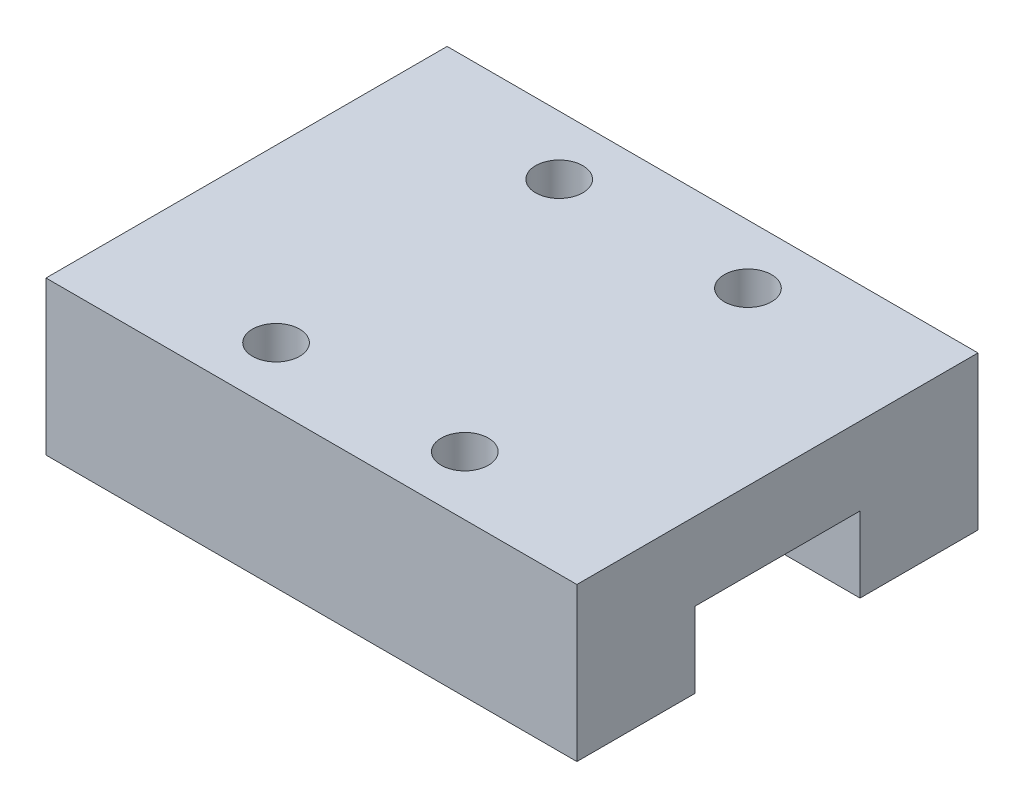
SolidWorks part; units mm, degrees
ref_plane "前视基准面" through (0, 0, 0) normal (0, 0, 1) x (1, 0, 0)
ref_plane "上视基准面" through (0, 0, 0) normal (0, 1, 0) x (1, 0, 0)
ref_plane "右视基准面" through (0, 0, 0) normal (1, 0, 0) x (0, 0, -1)
other "Configuration Table"
sketch "草图1" plane through (0, 0, 0) normal (0, 1, 0) x (1, 0, 0)
  line L1 (0, 0) -> (22.5, 0)
  line L2 (0, 0) -> (0, 17)
  line L3 (0, 17) -> (22.5, 17)
  line L4 (22.5, 0) -> (22.5, 17)
  line L5 (0, 0) -> (22.5, 17) construction
  line L6 (0, 17) -> (22.5, 0) construction
  point P4 (11.25, 8.5)
  dimension "D1" = 22.5
  dimension "D2" = 17
extrude "凸台-拉伸1" add sketch "草图1" along normal blind 6.5
sketch "草图2" plane through (0, 0, 0) normal (-1, 0, 0) x (0, 0, 1)
  line L0 (-8.5, 6.5) -> (-8.5, 0) construction
  line L1 (-17, 6.5) -> (0, 6.5) construction
  line L2 (-17, 0) -> (0, 0) construction
  line L4 (-12, 3.2) -> (-5, 3.2)
  line L5 (-12, 3.2) -> (-12, 0)
  line L6 (-12, 0) -> (-5, 0)
  line L7 (-5, 3.2) -> (-5, 0)
  line L8 (-12, 3.2) -> (-5, 0) construction
  line L9 (-12, 0) -> (-5, 3.2) construction
  point P10 (-8.5, 1.6)
  dimension "D1" = 3.2
  dimension "D2" = 7
extrude "切除-拉伸1" cut sketch "草图2" against normal through all
sketch "草图3" plane through (0, 6.5, 0) normal (0, 1, 0) x (1, 0, 0)
  line L0 (0, 8.5) -> (22.5, 8.5) construction
  line L1 (0, 17) -> (0, 0) construction
  line L2 (22.5, 0) -> (22.5, 17) construction
  line L3 (11.25, 17) -> (11.25, 0) construction
  line L4 (22.5, 17) -> (0, 17) construction
  line L5 (0, 0) -> (22.5, 0) construction
  circle A0 centre (7.25, 14.5) radius 1
  circle A1 centre (15.25, 14.5) radius 1
  circle A2 centre (15.25, 2.5) radius 1
  circle A3 centre (7.25, 2.5) radius 1
  dimension "D1" = 6
  dimension "D2" = 2
  dimension "D3" = 8
extrude "切除-拉伸2" cut sketch "草图3" against normal blind 2.4
